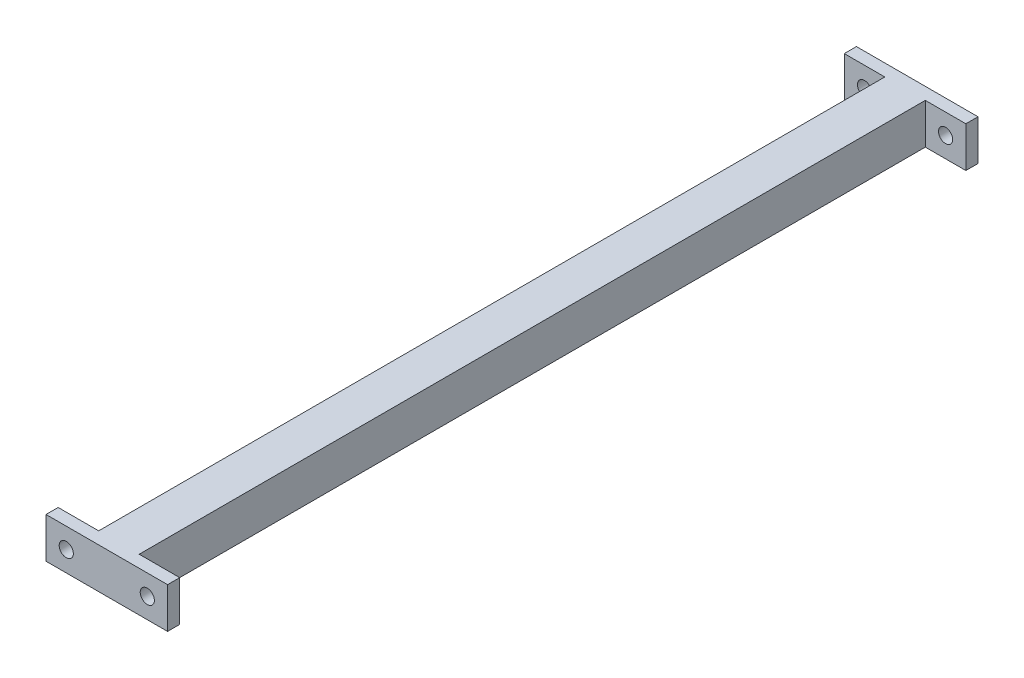
SolidWorks part; units mm, degrees
ref_plane "前视基准面" through (0, 0, 0) normal (0, 0, 1) x (1, 0, 0)
ref_plane "上视基准面" through (0, 0, 0) normal (0, 1, 0) x (1, 0, 0)
ref_plane "右视基准面" through (0, 0, 0) normal (1, 0, 0) x (0, 0, -1)
sketch "草图1" plane through (0, 0, 0) normal (0, 0, 1) x (1, 0, 0)
  line L0 (0, 5) -> (0, -5) construction
  line L5 (-5, -5) -> (5, -5)
  line L6 (-5, -5) -> (-5, 5)
  line L7 (-5, 5) -> (5, 5)
  line L8 (5, -5) -> (5, 5)
  line L9 (-5, -5) -> (5, 5) construction
  line L10 (-5, 5) -> (5, -5) construction
  line L12 (5, 5) -> (15, 5)
  line L13 (5, 5) -> (5, -5)
  line L14 (5, -5) -> (15, -5)
  line L15 (15, 5) -> (15, -5)
  line L16 (-5, 5) -> (-15, 5)
  line L17 (-5, 5) -> (-5, -5)
  line L18 (-5, -5) -> (-15, -5)
  line L19 (-15, 5) -> (-15, -5)
  circle A3 centre (10, 0) radius 1.75
  circle A4 centre (-10, 0) radius 1.75
  point P0 (0, 0)
  dimension "D3" = 5
  dimension "D4" = 3.5
  dimension "D5" = 5
  dimension "D6" = 5
  dimension "D7" = 5
  dimension "D1" = 10
  dimension "D2" = 10
extrude "凸台-拉伸1" add sketch "草图1" along normal blind 200 contours L5 L8 L7 L6 | L13 L12 L15 L14 | L17 L16 L19 L18 | A3 | A4
sketch "草图2" plane through (15, 0, 0) normal (1, 0, 0) x (0, 0, -1)
  line L0 (-200, 5) -> (0, 5) construction
  line L1 (-197, 5) -> (-3, 5)
  line L2 (-197, 5) -> (-197, -5)
  line L3 (-197, -5) -> (-3, -5)
  line L4 (-3, 5) -> (-3, -5)
  line L5 (-200, -5) -> (0, -5) construction
  line L6 (0, 5) -> (0, -5) construction
  line L7 (-200, 5) -> (-200, -5) construction
  dimension "D1" = 3
  dimension "D2" = 3
extrude "切除-拉伸1" cut sketch "草图2" against normal blind 10
sketch "草图3" plane through (-15, 0, 0) normal (-1, 0, 0) x (0, 0, 1)
  line L0 (200, 5) -> (0, 5) construction
  line L1 (3, 5) -> (197, 5)
  line L2 (3, 5) -> (3, -5)
  line L3 (3, -5) -> (197, -5)
  line L4 (197, 5) -> (197, -5)
  line L5 (200, -5) -> (0, -5) construction
  line L6 (200, 5) -> (200, -5) construction
  dimension "D1" = 3
  dimension "D2" = 3
extrude "切除-拉伸2" cut sketch "草图3" against normal blind 10
